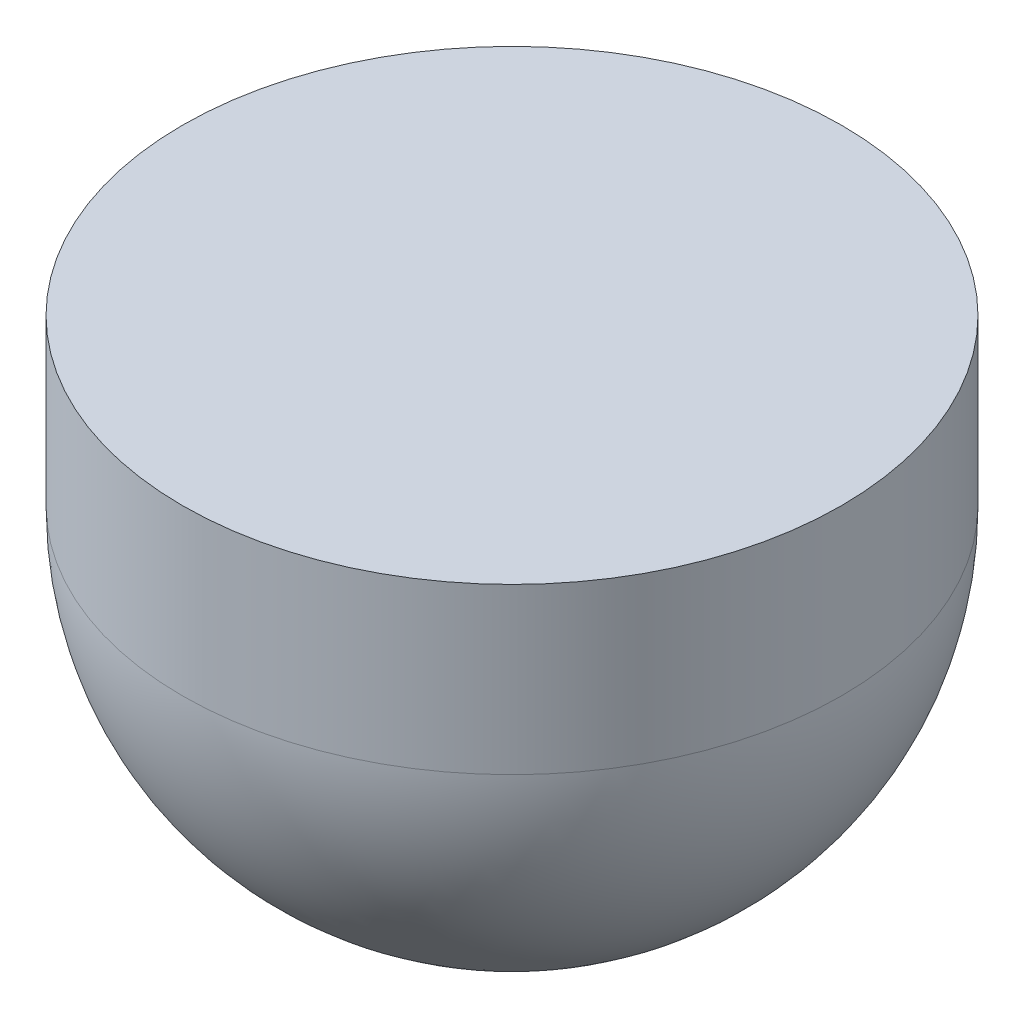
SolidWorks part; units mm, degrees
ref_plane "Front Plane" through (0, 0, 0) normal (0, 0, 1) x (1, 0, 0)
ref_plane "Top Plane" through (0, 0, 0) normal (0, 1, 0) x (1, 0, 0)
ref_plane "Right Plane" through (0, 0, 0) normal (1, 0, 0) x (0, 0, -1)
other "Center of Mass"
sketch "Sketch1" plane through (0, 0, 0) normal (0, 0, 1) x (1, 0, 0)
  line L0 (0, 0) -> (0, -16.8014)
  line L1 (0, -16.8014) -> (0, -30)
  line L2 (-20, -10) -> (-20, 0)
  line L3 (-20, 0) -> (0, 0)
  arc A0 (-20, -10) -> (0, -30) centre (0, -10) ccw
  dimension "D1" = 20
  dimension "D2" = 10
revolve "Revolve1" add sketch "Sketch1" angle 360 about L0
ref_point "Point1"
